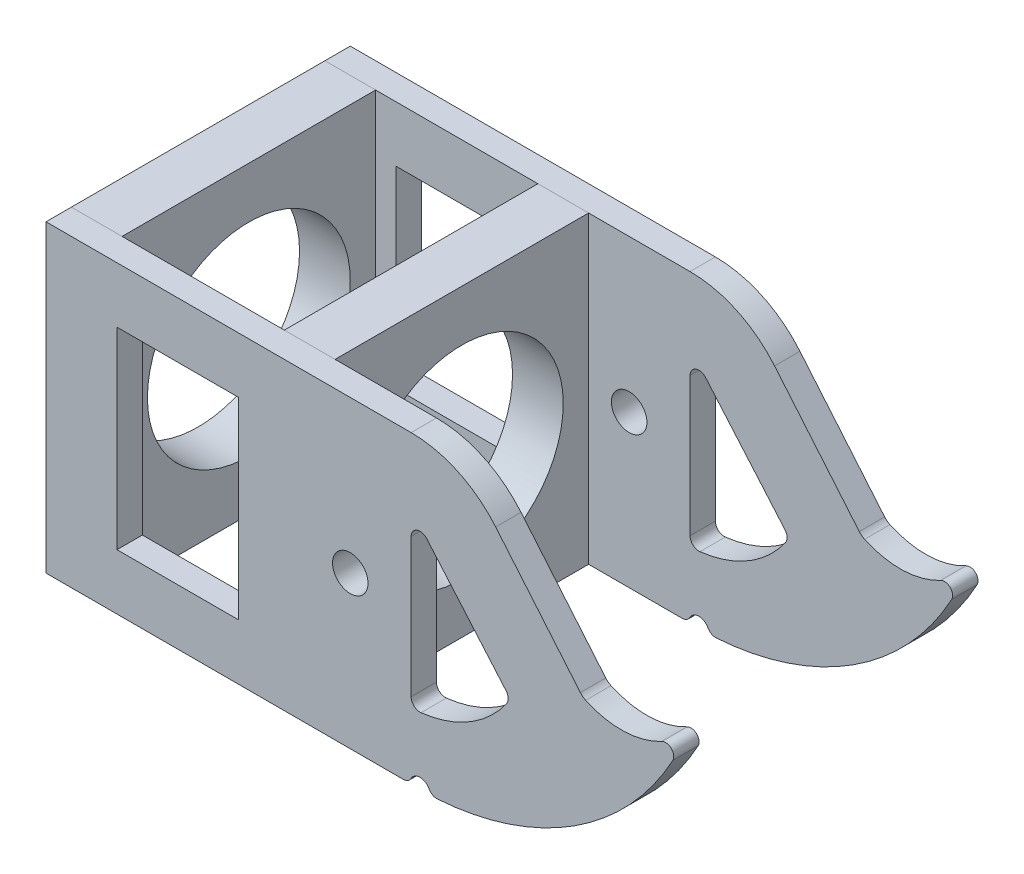
SolidWorks part; units mm, degrees
ref_plane "Front Plane" through (0, 0, 0) normal (0, 0, 1) x (1, 0, 0)
ref_plane "Top Plane" through (0, 0, 0) normal (0, 1, 0) x (1, 0, 0)
ref_plane "Right Plane" through (0, 0, 0) normal (1, 0, 0) x (0, 0, -1)
sketch "Sketch1" plane through (0, 0, 0) normal (0, 0, 1) x (1, 0, 0)
  line L0 (-23, -9.5) -> (-11, -9.5)
  line L5 (5.2187, -15) -> (-30, -15)
  line L6 (-30, 15) -> (6, 15)
  line L9 (-30, -15) -> (-30, 15)
  line L10 (6, 6.1305) -> (6, -7.5556)
  line L11 (-11, -9.5) -> (-11, 9.5)
  line L12 (-11, 9.5) -> (-23, 9.5)
  line L13 (-23, 9.5) -> (-23, -9.5)
  line L14 (7.5467, 6.705) -> (15.3563, -2.3589)
  line L15 (14.3393, 11.1079) -> (22.6888, 1.1436)
  arc A0 (6.9787, -8.43) -> (15.4088, -3.4406) centre (5.6375, 3.4524) ccw
  arc A1 (7.5467, 6.705) -> (6, 6.1305) centre (6.88, 6.1305) ccw
  arc A2 (15.4088, -3.4406) -> (15.3563, -2.3589) centre (14.6897, -2.9333) ccw
  arc A3 (6.9787, -8.43) -> (6, -7.5556) centre (6.88, -7.5556) cw
  arc A4 (7.7637, -14.5319) -> (5.9963, -14.5319) centre (6.88, -15) ccw
  arc A5 (5.9963, -14.5319) -> (5.2187, -15) centre (5.2187, -14.12) cw
  arc A6 (8.5413, -15) -> (7.7637, -14.5319) centre (8.5413, -14.12) cw
  arc A7 (8.5413, -15) -> (31.7978, -0.1018) centre (6.6418, 13.5662) ccw
  arc A8 (14.3393, 11.1079) -> (6, 15) centre (6, 4.12) ccw
  arc A9 (23.21, 0.745) -> (30.7141, 0.9838) centre (26.7236, 8.3593) ccw
  arc A10 (31.7978, -0.1018) -> (30.7141, 0.9838) centre (31.0948, 0.2802) ccw
  arc A11 (23.21, 0.745) -> (22.6888, 1.1436) centre (23.8385, 2.107) cw
  point P24 (5.88, -15)
  dimension "D1" = 0.88
  dimension "D2" = 0.88
  dimension "D5" = 10.88
  dimension "D6" = 0.8
extrude "Boss-Extrude1" add sketch "Sketch1" along normal blind 2.5
sketch "Sketch2" plane through (0, 0, 2.5) normal (0, 0, 1) x (1, 0, 0)
  line L1 (-30, 15) -> (-25, 15)
  line L2 (-30, 15) -> (-30, -15)
  line L3 (-30, -15) -> (-25, -15)
  line L4 (-25, 15) -> (-25, -15)
  line L6 (-9, 15) -> (-4, 15)
  line L7 (-9, 15) -> (-9, -15)
  line L8 (-9, -15) -> (-4, -15)
  line L9 (-4, 15) -> (-4, -15)
extrude "Boss-Extrude2" add sketch "Sketch2" along normal blind 25 separate body
ref_plane "Plane1" through (0, 0, 15) normal (0, 0, 1) x (1, 0, 0)
mirror "Mirror3" about plane through (0, 0, 15) normal (0, 0, 1) of bodies 101
sketch "Sketch3" plane through (-30, 0, 0) normal (-1, 0, 0) x (0, 0, 1)
  circle A0 centre (15, -0.0266) radius 10
extrude "Cut-Extrude1" cut sketch "Sketch3" against normal up to surface (26 mm away)
sketch "Sketch4" plane through (0, 0, 15) normal (0, 0, 1) x (1, 0, 0)
  circle A0 centre (0, 0) radius 1.75
extrude "Cut-Extrude2" cut sketch "Sketch4" against normal through all both and the other way through all
